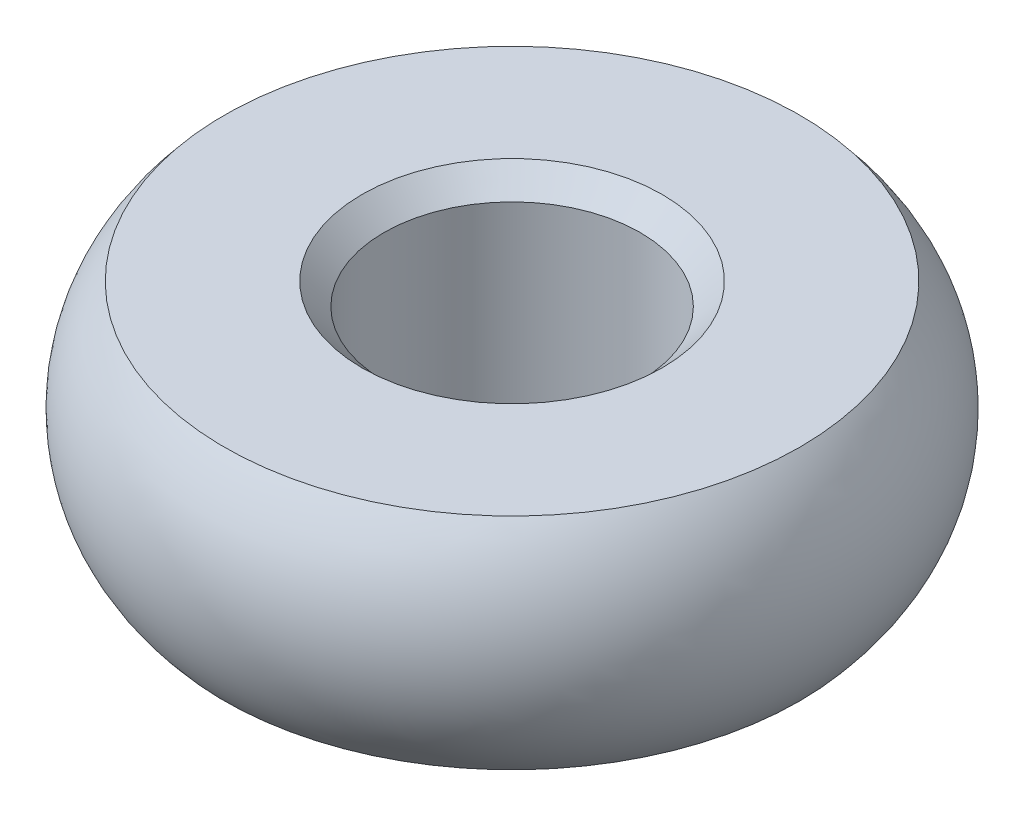
SolidWorks part; units mm, degrees
material "Custom Plastic"
ref_plane "Front Plane" through (0, 0, 0) normal (0, 0, 1) x (1, 0, 0)
ref_plane "Top Plane" through (0, 0, 0) normal (0, 1, 0) x (1, 0, 0)
ref_plane "Right Plane" through (0, 0, 0) normal (1, 0, 0) x (0, 0, -1)
sketch "Sketch1" plane through (0, 0, 0) normal (0, 0, 1) x (1, 0, 0)
  line L0 (0, -794.3764) -> (0, 38924.4445) construction
  line L1 (-794.3764, 0) -> (38924.4445, 0) construction
  line L2 (39.2705, 15) -> (17.5, 15)
  line L3 (17.5, 15) -> (17.5, -15)
  line L4 (17.5, -15) -> (39.2705, -15)
  arc A0 (39.2705, 15) -> (39.2705, -15) centre (22.5, 0) cw
  point P7 (17.5, 0)
  point P9 (45, 0)
  dimension "D3" = 22.5
  dimension "D1" = 30
  dimension "D2" = 17.5
  dimension "D4" = 90
revolve "Revolve1" add sketch "Sketch1" angle 360 about L0
chamfer "Chamfer1" distance 3 angle 45 2 edges at (17.5, 15, 0) (17.5, -15, 0)
